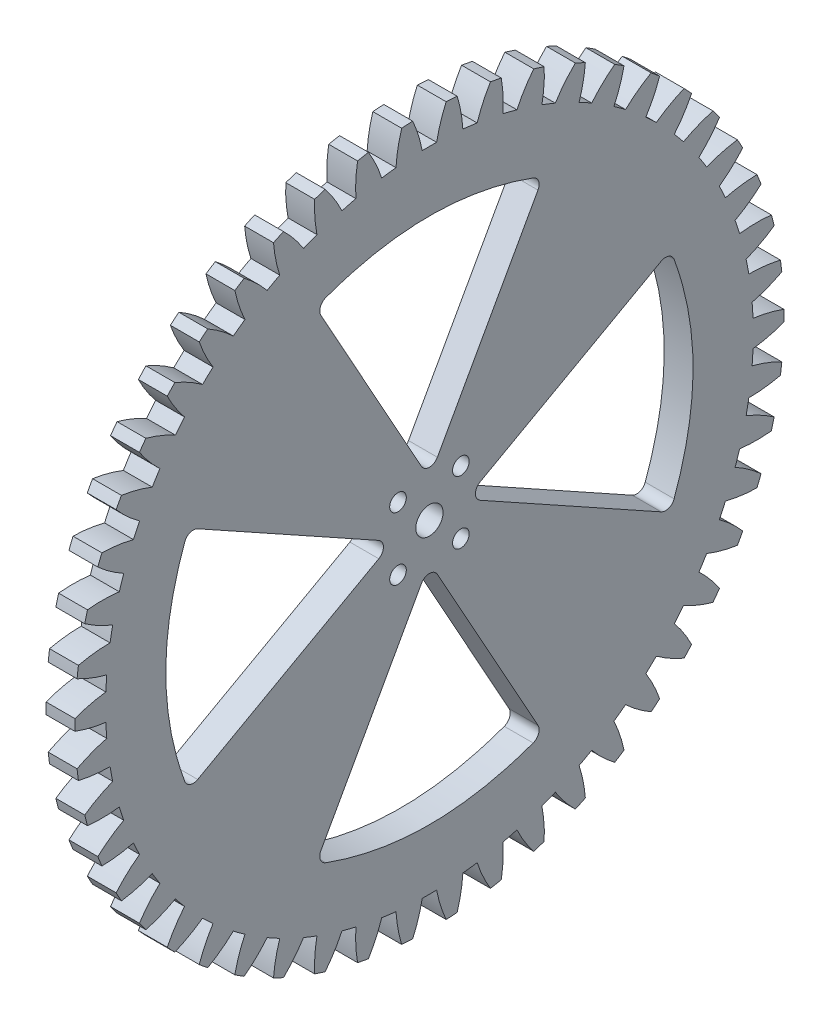
SolidWorks part; units mm, degrees
ref_plane "Plane1" through (0, 0, 0) normal (0, 0, 1) x (1, 0, 0)
ref_plane "Plane2" through (0, 0, 0) normal (0, 1, 0) x (1, 0, 0)
ref_plane "Plane3" through (0, 0, 0) normal (1, 0, 0) x (0, 0, -1)
sketch "HoldingSke" plane through (0, 0, 0) normal (0, 1, 0) x (1, 0, 0)
  line L0 (0, 0) -> (0.2143, -0.2553)
  line L1 (-15, 0) -> (100, 0) construction
  line L2 (0, 0) -> (-2.1039, 2.3779)
  line L3 (0, 0) -> (-11.863, 4.5341)
  line L4 (0, 0) -> (5.5511, 6.6156)
  line L5 (0, 0) -> (-46.8476, -17.4728)
  line L6 (0, 0) -> (-5.2639, -3.5516)
  line L7 (-2.1039, 2.3779) -> (8.6586, 51.206)
  line L8 (-76.2, 54.61) -> (-75.2, 54.61)
  line L9 (-67.7845, 28.3722) -> (-49.3413, 33.142)
  line L10 (-76.2, 71.12) -> (104.1128, 71.12)
  line L11 (0, 0) -> (-6.35, 0)
  line L12 (-76.2, 101.6) -> (-76.093, 101.6)
  line L13 (24.9733, 27.94) -> (52.9518, 28.4284)
  line L14 (24.9733, 27.94) -> (24.9743, 27.94)
  line L15 (24.9733, 27.94) -> (100.4006, 29.5858)
  line L16 (-63.627, -3) -> (-12.827, -3)
  circle A0 centre (0, 0) radius 3
  circle A1 centre (0, 0) radius 37.5
  circle A2 centre (0, 0) radius 37.5
  circle A3 centre (0, 0) radius 3
  dimension "MHD" = 75
  dimension "Hub_dia" = 75
  dimension "Bore" = 6
  dimension "MBD" = 6
  dimension "Num_teeth" = 50
  dimension "Pitch" = 0.3333
  dimension "Overall_len" = 50
  dimension "Show_teeth" = 50
  dimension "Thickness" = 6.35
  dimension "OAL" = 50.0002
  dimension "T_dim" = 1
  dimension "Ap" = 14.5
  dimension "H" = 19.05
  dimension "Pitch_radius" = 180.3128
  dimension "Width" = 6.35
  dimension "Backlash" = 0.107
  dimension "Addendum_fac" = 1
  dimension "Dedendum_fac" = 1.25
  dimension "Clearance_fac" = 0.25
  dimension "Dedendum_add" = 0.001
  dimension "Module" = 3
sketch "BasProSke" plane through (0, 0, 0) normal (0, 1, 0) x (1, 0, 0)
  line L0 (-10, 0) -> (60, 0) construction
  line L1 (0, 0) -> (0, 78)
  line L2 (0, 0) -> (6.35, 0)
  line L3 (6.35, 0) -> (6.35, 78)
  line L4 (6.35, 78) -> (0, 78)
  dimension "Thickness" = 6.35
  dimension "Diameter" = 156
revolve "Base-Revolve" add sketch "BasProSke" angle 360 about L0
sketch "TooCutSke" plane through (0, 0, 0) normal (1, 0, 0) x (0, 0, -1)
  line L1 (0, 0) -> (0, 107) construction
  line L2 (0, 0) -> (-2.543, 74.9569) construction
  line L3 (0, 0) -> (-9.4146, 149.6414) construction
  line L4 (-2.543, 74.9569) -> (-4.7073, 74.8207) construction
  arc A0 (1.5844, 71.2314) -> (-1.5844, 71.2314) centre (0, 0) ccw
  arc A1 (3.6968, 77.9378) -> (-3.6968, 77.9378) centre (0, 0) ccw
  circle A2 centre (0, 0) radius 75 construction
  circle A3 centre (0, 0) radius 72.6111 construction
  arc A4 (-1.5844, 71.2314) -> (-3.6968, 77.9378) centre (-31.0576, 65.6338) ccw
  arc A5 (3.6968, 77.9378) -> (1.5844, 71.2314) centre (31.0576, 65.6338) ccw
  dimension "Root_dia" = 142.498
  dimension "Overcut_dia" = 156.0508
  dimension "Pitch_dia" = 150
  dimension "Base_dia" = 145.2221
  dimension "Flank_rad" = 30
  dimension "Half_ang" = 3.6
  dimension "Half_CT" = 2.1686
extrude "ToothCut" cut sketch "TooCutSke" along normal through all
fillet "Breaks" [suppressed] radius 0.06
fillet "RootFillets" [suppressed] radius 0.751
pattern_circular "TeethCuts" count 50 over 360 about axis through (0, 0, 0) along (1, 0, 0) of "ToothCut", "RootFillets", "Breaks"
sketch "HubNeaOneSke" plane through (0, 0, 0) normal (-1, 0, 0) x (0, 0, 1)
  circle A0 centre (0, 0) radius 37.5
  dimension "Diameter" = 75
extrude "HubNearOne" [suppressed] add sketch "HubNeaOneSke" along normal blind 43.6502
sketch "HubNeaBotSke" plane through (0, 0, 0) normal (-1, 0, 0) x (0, 0, 1)
  circle A0 centre (0, 0) radius 37.5
  dimension "Diameter" = 75
extrude "HubNearBoth" [suppressed] add sketch "HubNeaBotSke" along normal blind 21.8251
ref_plane "FarPln" through (6.35, 0, 0) normal (1, 0, 0) x (0, 0, -1)
sketch "HubFarSke" plane through (6.35, 0, 0) normal (1, 0, 0) x (0, 0, -1)
  circle A0 centre (0, 0) radius 37.5
  dimension "Diameter" = 75
extrude "HubFar" [suppressed] add sketch "HubFarSke" along normal blind 21.8251
sketch "BorSke" plane through (0, 0, 0) normal (1, 0, 0) x (0, 0, -1)
  circle A0 centre (0, 0) radius 3
  dimension "Diameter" = 6
extrude "Bore" cut sketch "BorSke" along normal mid plane 100.0004
sketch "KeySke" plane through (0, 0, 0) normal (1, 0, 0) x (0, 0, -1)
  line L0 (-1, 0) -> (-1, 4)
  line L1 (-1, 4) -> (1, 4)
  line L2 (1, 4) -> (1, 0)
  line L3 (0, 0) -> (0, 34) construction
  line L4 (-1, 0) -> (1, 0)
  dimension "Offset" = 4
  dimension "Width" = 2
extrude "Keyway" [suppressed] cut sketch "KeySke" along normal mid plane 100.0004
pattern_circular "Keyway2" [suppressed] count 2 every 90 about axis through (-10, 0, 0) along (1, 0, 0)
sketch "Esquisse1" plane through (0, 0, 0) normal (-1, 0, 0) x (0, 0, 1)
  circle A0 centre (6.9148, 6.9148) radius 1.83
  dimension "D1" = 3.66
extrude "Enlèv. mat.-Extru.1" cut sketch "Esquisse1" against normal up to next
pattern_circular "Répétition circulaire1" count 4 every 90 about axis through (0, 0, 0) along (1, 0, 0) of "Enlèv. mat.-Extru.1"
sketch "Esquisse2" plane through (6.35, 0, 0) normal (1, 0, 0) x (0, 0, -1)
  line L0 (-53, 25) -> (-8, 0)
  line L1 (-8, 0) -> (-53, -25)
  line L2 (-53, -25) -> (-53, 25) construction
  line L3 (-53, 0) -> (-8, 0) construction
  line L4 (50, 0) -> (-50, 0) construction
  circle A0 centre (0, 0) radius 3 construction
  spline S0 degree 2 poles (-53, 25) (-63, 0) (-53, -25) knots 0 0 0 1 1 1
  dimension "D4" = 8
  dimension "D1" = 45
  dimension "D2" = 50
  dimension "D3" = 5
extrude "Enlèv. mat.-Extru.2" cut sketch "Esquisse2" against normal up to next
fillet "Congé1" radius 2 3 edges at (3.175, -25, 53) (3.175, 25, 53) (3.175, 0, 8)
pattern_circular "Répétition circulaire2" count 4 every 90 about axis through (6.35, 0, 0) along (-1, 0, 0) of "Congé1", "Enlèv. mat.-Extru.2"
equation "' \"Module@HoldingSke\" = 6.35"
equation "' \"Num_teeth@HoldingSke\" = 12"
equation "' \"Ap@HoldingSke\" =  20"
equation "' \"Ap@HoldingSke\" = 20"
equation "' \"Width@HoldingSke\" = 0.5 * 25.4"
equation "' \"Hub_dia@HoldingSke\"= 1 * 25.4"
equation "' \"Hub_dia@HoldingSke\" = 1 * 25.4"
equation "' \"Overall_len@HoldingSke\" = 1.0 * 25.4"
equation "' \"Bore@HoldingSke\" = 0.75 * 25.4"
equation "' \"T_dim@HoldingSke\" = 0.1 * 25.4"
equation "' \"Width@KeySke\" = 0.25 * 25.4"
equation "' \"Show_teeth@HoldingSke\" = 13"
equation "' \"Backlash@HoldingSke\" = 0.009 * 25.4"
equation "' \"Addendum_fac@HoldingSke\" = 1.0"
equation "' \"Dedendum_fac@HoldingSke\" = 1.25"
equation "' \"Dedendum_add@HoldingSke\" = 0.00005 * 25.4"
equation "' \"Clearance_fac@HoldingSke\" = 0.25"
equation "\"Pitch@HoldingSke\" = 1 / \"Module@HoldingSke\""
equation "\"Overcut_dia@TooCutSke\" = (\"Num_teeth@HoldingSke\" + 2 * \"Addendum_fac@HoldingSke\") / \"Pitch@HoldingSke\" + 0.002 * 25.4"
equation "\"Pitch_dia@TooCutSke\" = \"Num_teeth@HoldingSke\" / \"Pitch@HoldingSke\""
equation "\"Base_dia@TooCutSke\" = \"Num_teeth@HoldingSke\" / \"Pitch@HoldingSke\" * cos((\"Ap@HoldingSke\"  * 3.14159265 / 180))"
equation "\"Root_dia@TooCutSke\" = (\"Num_teeth@HoldingSke\" + 2) / \"Pitch@HoldingSke\" - 2 * (\"Addendum_fac@HoldingSke\" + \"Dedendum_fac@HoldingSke\") / \"Pitch@HoldingSke\" - \"Dedendum_add@HoldingSke\" * 2"
equation "\"Half_ang@TooCutSke\" = 180 / \"Num_teeth@HoldingSke\""
equation "\"Half_CT@TooCutSke\" = \"Num_teeth@HoldingSke\" / \"Pitch@HoldingSke\" * sin((3.14159265 / 2 / \"Num_teeth@HoldingSke\")) / 2 - 7 * \"Backlash@HoldingSke\" / 4"
equation "\"Flank_rad@TooCutSke\" = \"Num_teeth@HoldingSke\" / \"Pitch@HoldingSke\" / 5"
equation "\"Radius@RootFillets\" = \"Clearance_fac@HoldingSke\" / \"Pitch@HoldingSke\" + \"Dedendum_add@HoldingSke\""
equation "\"Break_rad@Breaks\" = 0.02 / \"Pitch@HoldingSke\""
equation "\"Thickness@HoldingSke\" = \"Width@HoldingSke\""
equation "\"OAL@HoldingSke\" = \"Thickness@HoldingSke\""
equation "\"MHD@HoldingSke\" = (\"Num_teeth@HoldingSke\" + 2) / \"Pitch@HoldingSke\" - 2 * (\"Addendum_fac@HoldingSke\" + \"Dedendum_fac@HoldingSke\")  / \"Pitch@HoldingSke\" - \"Dedendum_add@HoldingSke\" * 2"
equation "\"MBD@HoldingSke\" = (\"Num_teeth@HoldingSke\" + 2) / \"Pitch@HoldingSke\" - 2 * (\"Addendum_fac@HoldingSke\" + \"Dedendum_fac@HoldingSke\")  / \"Pitch@HoldingSke\" - \"Dedendum_add@HoldingSke\" * 2 - 0.002 * 25.4"
equation "\"MHD@HoldingSke\" = ((sgn( \"MHD@HoldingSke\" - \"Hub_dia@HoldingSke\" )-1)*( \"MHD@HoldingSke\" - \"Hub_dia@HoldingSke\" ))/-2+ \"Hub_dia@HoldingSke\""
equation "\"MBD@HoldingSke\" = ((sgn( \"MBD@HoldingSke\" - \"Bore@HoldingSke\" )-1)*( \"MBD@HoldingSke\" - \"Bore@HoldingSke\" ))/-2+ \"Bore@HoldingSke\""
equation "\"OAL@HoldingSke\" = ((sgn( \"OAL@HoldingSke\" - \"Overall_len@HoldingSke\" )+1)*( \"OAL@HoldingSke\" - \"Overall_len@HoldingSke\" ))/2 + \"Overall_len@HoldingSke\" + 0.000002 * 25.4"
equation "\"Num_teeth@TeethCuts\" = int( \"Show_teeth@HoldingSke\" ) + 1"
equation "\"Num_teeth@TeethCuts\" = ((sgn( \"Num_teeth@TeethCuts\" - \"Num_teeth@HoldingSke\" )-1)*( \"Num_teeth@TeethCuts\" - \"Num_teeth@HoldingSke\" ))/-2+ \"Num_teeth@HoldingSke\""
equation "\"Num_teeth@TeethCuts\" = ((sgn( \"Num_teeth@TeethCuts\" - 2.0)+1)*( \"Num_teeth@TeethCuts\" - 2.0))/2 +2.0"
equation "\"Angle@TeethCuts\" = 360.0 / \"Num_teeth@HoldingSke\""
equation "\"Diameter@BasProSke\" = (\"Num_teeth@HoldingSke\" + 2 * \"Addendum_fac@HoldingSke\") / \"Pitch@HoldingSke\""
equation "\"Thickness@BasProSke\"  = \"Thickness@HoldingSke\""
equation "' \"Fillet_rad@BasProSke\" =  \"Thickness@HoldingSke\" * 0.05"
equation "' \"Fillet_rad@BasProSke\" = \"Thickness@HoldingSke\" * 0.05"
equation "\"MHD@HoldingSke\" = ((sgn( \"MHD@HoldingSke\" - \"Root_dia@TooCutSke\" )-1)*( \"MHD@HoldingSke\" - \"Root_dia@TooCutSke\" ))/-2+ \"Root_dia@TooCutSke\""
equation "\"Diameter@HubNeaOneSke\" = \"MHD@HoldingSke\""
equation "\"Length@HubNearOne\" = \"OAL@HoldingSke\" - \"Thickness@BasProSke\""
equation "\"Diameter@HubNeaBotSke\" = \"MHD@HoldingSke\""
equation "\"Length@HubNearBoth\" = ( \"OAL@HoldingSke\" - \"Thickness@BasProSke\" ) / 2.0"
equation "\"Thickness@FarPln\" = \"Thickness@BasProSke\""
equation "\"Diameter@HubFarSke\" = \"MHD@HoldingSke\""
equation "\"Length@HubFar\" = ( \"OAL@HoldingSke\" - \"Thickness@BasProSke\" ) / 2.0"
equation "\"Diameter@BorSke\" = \"MBD@HoldingSke\""
equation "\"D1@Bore\" = \"OAL@HoldingSke\" * 2.0"
equation "\"D1@Keyway\" = \"OAL@HoldingSke\" * 2.0"
equation "\"Offset@KeySke\" = \"T_dim@HoldingSke\" + \"MBD@HoldingSke\" / 2.0"
